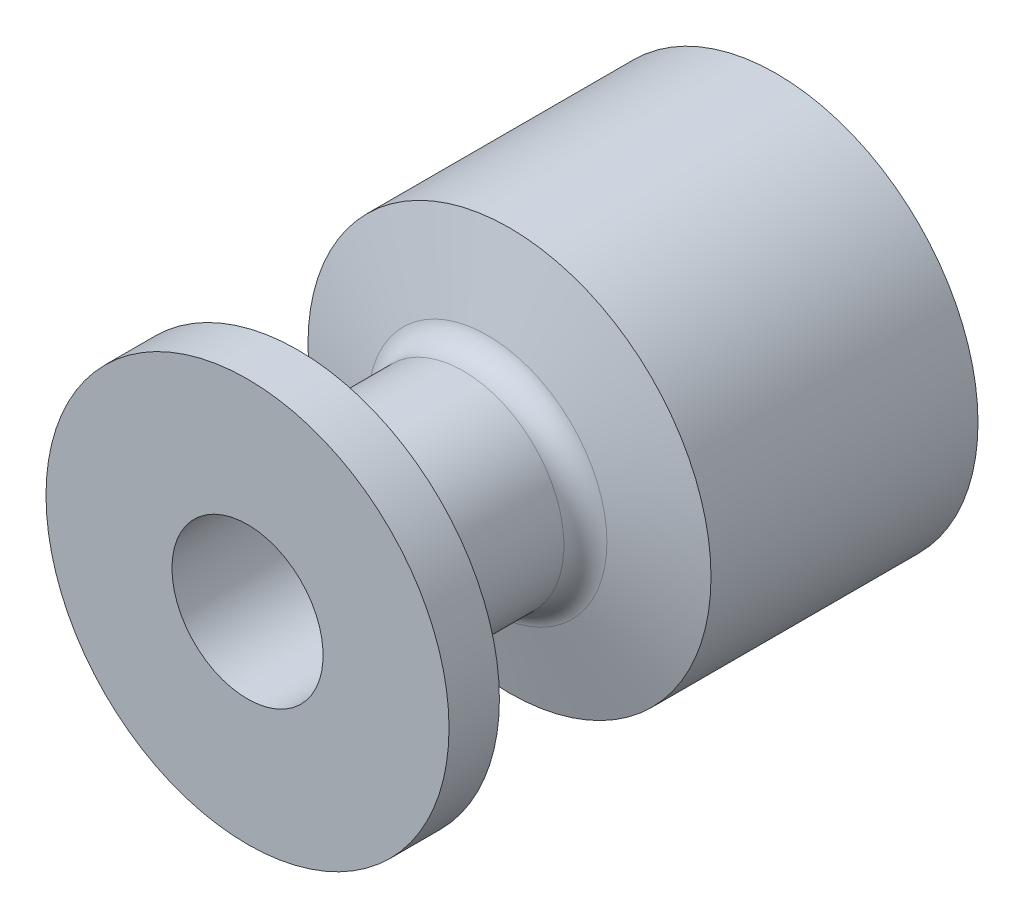
SolidWorks part; units mm, degrees
material "6061 合金"
ref_plane "前视基准面" through (0, 0, 0) normal (0, 0, 1) x (1, 0, 0)
ref_plane "上视基准面" through (0, 0, 0) normal (0, 1, 0) x (1, 0, 0)
ref_plane "右视基准面" through (0, 0, 0) normal (1, 0, 0) x (0, 0, -1)
sketch "草图1" plane through (0, 0, 0) normal (0, 0, 1) x (1, 0, 0)
  circle A0 centre (0, 0) radius 4
  circle A1 centre (0, 0) radius 1.5
  dimension "D1" = 8
  dimension "D2" = 3
extrude "凸台-拉伸1" add sketch "草图1" along normal blind 10.5
sketch "草图3" plane through (0, 0, 0) normal (0, 1, 0) x (1, 0, 0)
  line L0 (-3.6246, 0) -> (-2.85, -0.65)
  line L1 (4, 0) -> (-4, 0) construction
  line L2 (-2.85, -0.65) -> (0, -0.65)
  line L4 (0, 0) -> (0, -8.2003) construction
  line L6 (-3.6246, 0) -> (0, 0)
  line L7 (-4, 0) -> (-4, -10.5) construction
  line L9 (-4, -5.3) -> (-4, -9.5)
  line L10 (-2, -5.8359) -> (-2, -8.8502)
  line L11 (-4, -5.3) -> (-2, -5.8359)
  line L12 (0, -6.3718) -> (0, -8.2003) construction
  line L14 (-4, -9.5) -> (-2, -8.8502)
  line L15 (-4, -10.5) -> (4, -10.5) construction
  line L16 (0, -0.65) -> (0, 0)
  dimension "D1" = 2.85
  dimension "D2" = 3.6246
  dimension "D3" = 0.65
  dimension "D4" = 75
  dimension "D5" = 72
  dimension "D6" = 4.2
  dimension "D7" = 1
  dimension "D8" = 2
revolve "切除-旋转1" cut sketch "草图3" angle 360 about L4
fillet "圆角1" radius 0.5 2 edges at (-2, 0, 8.8502) (-2, 0, 5.8359)
